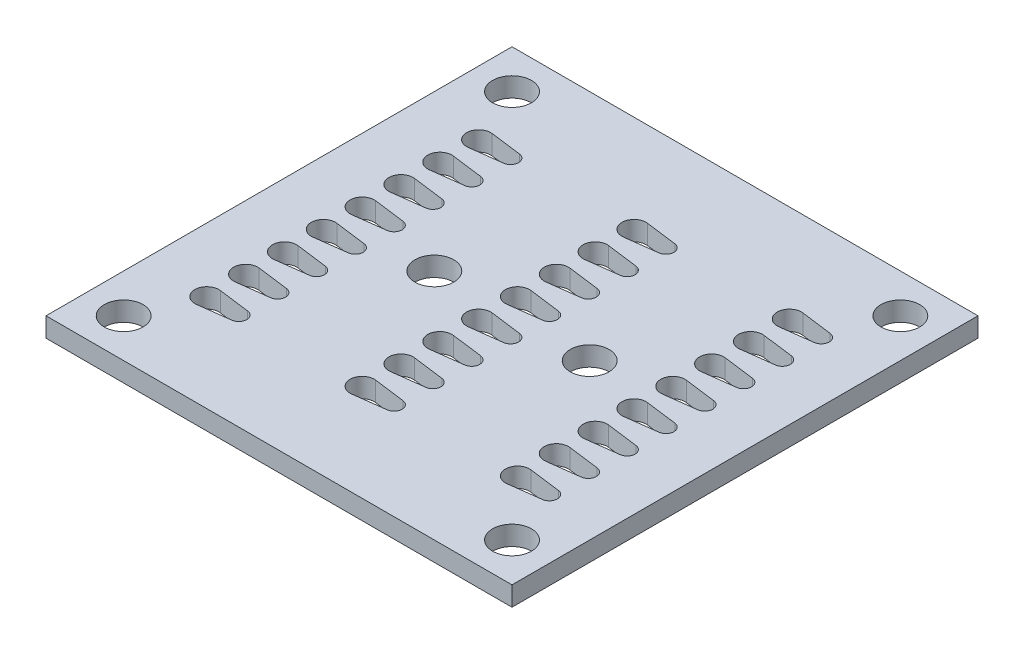
SolidWorks part; units mm, degrees
ref_plane "Front Plane" through (0, 0, 0) normal (0, 0, 1) x (1, 0, 0)
ref_plane "Top Plane" through (0, 0, 0) normal (0, 1, 0) x (1, 0, 0)
ref_plane "Right Plane" through (0, 0, 0) normal (1, 0, 0) x (0, 0, -1)
sketch "BaseWith Alignment" plane through (0, 0, 0) normal (0, 1, 0) x (1, 0, 0)
  line L0 (-6.35, 15.875) -> (-6.35, -60.325) construction
  line L1 (-12.7, 15.875) -> (63.5, 15.875)
  line L2 (-12.7, 15.875) -> (-12.7, -60.325)
  line L3 (-12.7, -60.325) -> (63.5, -60.325)
  line L4 (63.5, 15.875) -> (63.5, -60.325)
  line L5 (57.15, 15.875) -> (57.15, -60.325) construction
  line L6 (-6.35, 9.525) -> (57.15, 9.525) construction
  line L7 (-6.35, -53.975) -> (57.15, -53.975) construction
  line L8 (-12.7, -22.225) -> (63.5, -22.225) construction
  circle A0 centre (-6.35, 9.525) radius 3.175
  circle A1 centre (57.15, 9.525) radius 3.175
  circle A2 centre (-6.35, -53.975) radius 3.175
  circle A3 centre (57.15, -53.975) radius 3.175
  circle A4 centre (12.7, -22.225) radius 3.175
  circle A5 centre (38.1, -22.225) radius 3.175
  dimension "D3" = 6.35
  dimension "D1" = 76.2
  dimension "D2" = 76.2
  dimension "D4" = 6.35
  dimension "D5" = 6.35
  dimension "D6" = 6.35
  dimension "D7" = 6.35
  dimension "D8" = 25.4
  dimension "D9" = 25.4
  dimension "D10" = 12.7
  dimension "D11" = 9.525
extrude "Boss-Extrude1" add sketch "BaseWith Alignment" along normal blind 3.175
sketch "Sketch1" plane through (0, 0, 0) normal (0, -1, 0) x (-1, 0, 0)
  line L0 (-3, 0) -> (3, 0) construction
  line L1 (-3, 1.25) -> (3, 1.25) construction
  line L2 (-3, -1.25) -> (3, -1.25) construction
  line L22 (0.5, 0) -> (0.3393, 1.2396) construction
  line L23 (2.0179, 1.9614) -> (2.0179, -1.9614) construction
  line L25 (2.0179, -1.9614) -> (-3.1107, -1.2965)
  line L27 (2.0179, 1.9614) -> (-3.1107, 1.2965)
  line L28 (-3.1107, 1.2965) -> (-3.1107, -1.2965) construction
  line L29 (-3, 0) -> (-3.0386, 0.2975) construction
  line L30 (0.3393, 1.2396) -> (0.275, 1.7355) construction
  line L31 (-3.0386, 0.2975) -> (-3.1671, 1.2892) construction
  arc A0 (-3, 1.25) -> (-3, -1.25) centre (-3, 0) ccw construction
  arc A1 (3, -1.25) -> (3, 1.25) centre (3, 0) ccw construction
  circle A2 centre (0.5, 0) radius 0.762 construction
  circle A3 centre (3, 0) radius 0.3 construction
  circle A4 centre (-3, 0) radius 0.3 construction
  arc A7 (-3.1, 0.2828) -> (-2.7, 0) centre (-3, 0) ccw construction
  circle A8 centre (0.5, 0) radius 1.25 construction
  circle A9 centre (0.5, 0) radius 1 construction
  arc A12 (2.0179, 1.9614) -> (2.0179, -1.9614) centre (2.2722, 0) cw
  arc A13 (-3.1107, 1.2965) -> (-3.1107, -1.2965) centre (-2.9426, 0) ccw
  point P2 (0, 0)
  point P25 (2.0179, 0)
  point P29 (-3.0543, 0)
  point P31 (-3.1107, 0)
  dimension "D3" = 0.6
  dimension "D5" = 1.524
  dimension "D6" = 0.6
  dimension "D7" = 2.5
  dimension "D8" = 2
  dimension "D2" = 2.5
  dimension "D4" = 2.5
  dimension "D1" = 3.5
  dimension "D10" = 3.9229
  dimension "D9" = 0.5
  dimension "D11" = 1
extrude "Cut-Extrude6" cut sketch "Sketch1" against normal through all
pattern_linear "LPattern1" count 8 spacing 6.35 along (0, 0, 1) count 3 spacing 25.4 along (1, 0, 0) of "Cut-Extrude6"
equation "\"StabilizerRodeHole\"=0.6"
equation "\"D3@Sketch1\"=\"StabilizerRodeHole\""
equation "\"D6@Sketch1\"=\"StabilizerRodeHole\""
